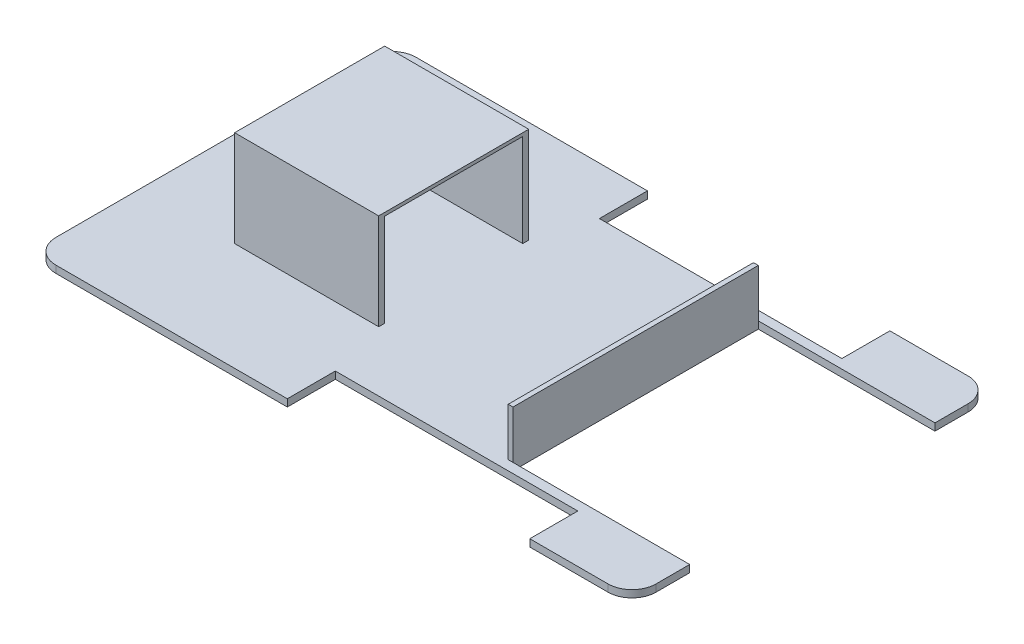
SolidWorks part; units mm, degrees
ref_plane "Front Plane" through (0, 0, 0) normal (0, 0, 1) x (1, 0, 0)
ref_plane "Top Plane" through (0, 0, 0) normal (0, 1, 0) x (1, 0, 0)
ref_plane "Right Plane" through (0, 0, 0) normal (1, 0, 0) x (0, 0, -1)
sketch "Sketch1" plane through (0, 0, 0) normal (0, 1, 0) x (1, 0, 0)
  line L0 (106.4075, 20) -> (207.4075, 20)
  line L1 (0, 0) -> (106.4075, 0)
  line L2 (0, 0) -> (0, 150)
  line L3 (0, 150) -> (106.4075, 150)
  line L4 (250, 0) -> (250, 24.022)
  line L6 (106.4075, 150) -> (106.4075, 130)
  line L7 (106.4075, 130) -> (207.4075, 130)
  line L8 (207.4075, 150) -> (207.4075, 130)
  line L9 (106.4075, 20) -> (106.4075, 0)
  line L11 (207.4075, 20) -> (207.4075, 0)
  line L12 (207.4075, 150) -> (250, 150)
  line L13 (207.4075, 0) -> (250, 0)
  line L14 (250, 126.1915) -> (250, 150)
  line L15 (250, 126.1915) -> (176.3974, 126.1915)
  line L17 (250, 24.022) -> (176.3974, 24.022)
  line L18 (176.3974, 126.1915) -> (176.3974, 24.022)
  dimension "D1" = 250
  dimension "D2" = 150
  dimension "D3" = 101
  dimension "D4" = 20
extrude "Boss-Extrude1" add sketch "Sketch1" along normal blind 3
sketch "Sketch2" plane through (0, 3, 0) normal (0, 1, 0) x (1, 0, 0)
  line L8 (99.461, 105) -> (39.461, 105)
  line L9 (99.461, 47.5) -> (39.461, 47.5)
  line L10 (99.461, 47.5) -> (99.461, 45)
  line L11 (99.461, 45) -> (39.461, 45)
  line L12 (39.461, 47.5) -> (39.461, 45)
  line L13 (99.461, 105) -> (99.461, 107.5)
  line L14 (99.461, 107.5) -> (39.461, 107.5)
  line L15 (39.461, 105) -> (39.461, 107.5)
  line L16 (106.4075, 150) -> (0, 150) construction
  dimension "D1" = 60
  dimension "D2" = 2.5
  dimension "D3" = 60
  dimension "D4" = 42.5
extrude "Boss-Extrude2" add sketch "Sketch2" along normal blind 40
sketch "Sketch5" plane through (0, 0, -47.5) normal (0, 0, -1) x (-1, 0, 0)
  line L0 (-39.461, 43) -> (-39.461, 3) construction
  line L1 (-99.461, 43) -> (-39.461, 43)
  line L2 (-99.461, 43) -> (-99.461, 41.6404)
  line L3 (-99.461, 41.6404) -> (-39.461, 41.6404)
  line L4 (-39.461, 43) -> (-39.461, 41.6404)
extrude "Boss-Extrude5" add sketch "Sketch5" along normal up to surface (57.5 mm away) contours L3 L4 L1 L2 up to face at (69.461, 23, -105)
fillet "Fillet1" radius 10 4 edges at (250, 1.5, 0) (0, 1.5, -150) (0, 1.5, 0) (250, 1.5, -150)
sketch "Sketch6" plane through (0, 3, 0) normal (0, 1, 0) x (1, 0, 0)
  line L1 (176.3974, 126.1915) -> (174.3974, 126.1915)
  line L2 (176.3974, 126.1915) -> (176.3974, 24.022)
  line L3 (176.3974, 24.022) -> (174.3974, 24.022)
  line L4 (174.3974, 126.1915) -> (174.3974, 24.022)
  dimension "D1" = 2
extrude "Boss-Extrude6" add sketch "Sketch6" along normal blind 20
